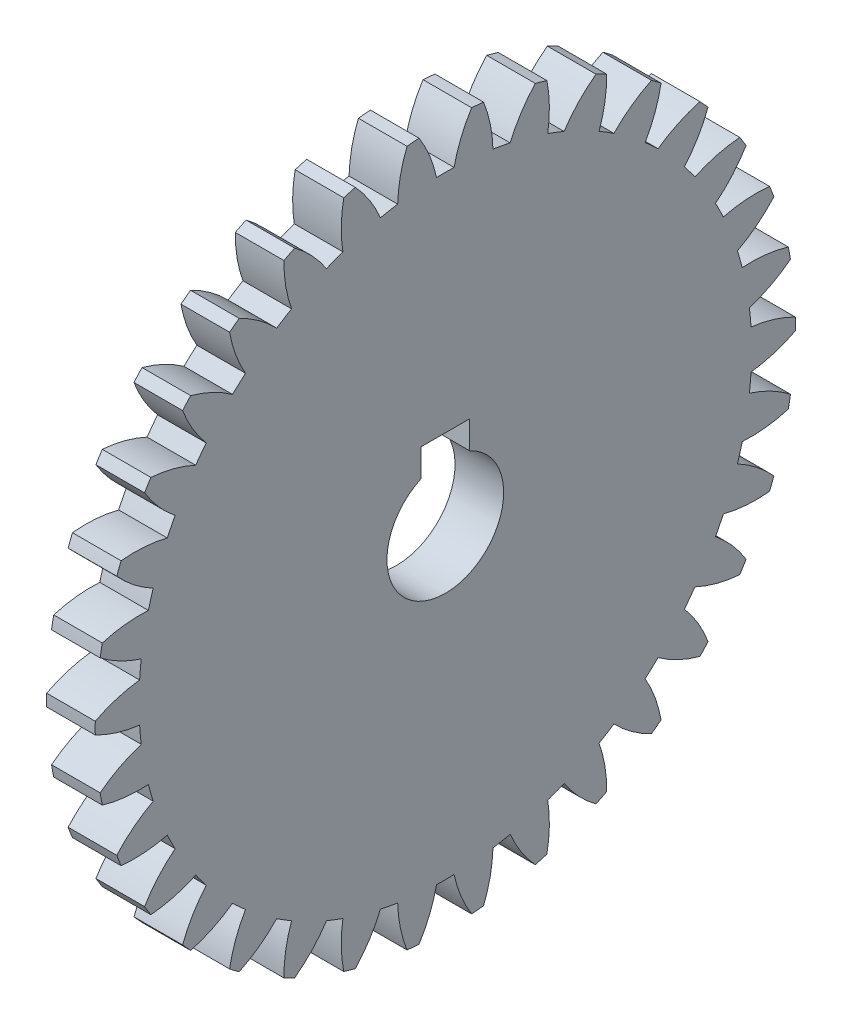
SolidWorks part; units mm, degrees
ref_plane "Plane1" through (0, 0, 0) normal (0, 0, 1) x (1, 0, 0)
ref_plane "Plane2" through (0, 0, 0) normal (0, 1, 0) x (1, 0, 0)
ref_plane "Plane3" through (0, 0, 0) normal (1, 0, 0) x (0, 0, -1)
other "Configuration Table"
sketch "HoldingSke" plane through (0, 0, 0) normal (0, 1, 0) x (1, 0, 0)
  line L0 (0, 0) -> (0.4145, -0.2796)
  line L1 (-15, 0) -> (100, 0) construction
  line L2 (0, 0) -> (-2.1039, 2.3779)
  line L3 (0, 0) -> (-11.863, 4.5341)
  line L4 (0, 0) -> (7.1596, 4.8292)
  line L5 (0, 0) -> (-46.8476, -17.4728)
  line L6 (0, 0) -> (-4.1448, -2.7965)
  line L7 (-2.1039, 2.3779) -> (8.6586, 51.2059)
  line L8 (-76.2, 54.61) -> (-73.9, 54.61)
  line L9 (-71.009, 38.7566) -> (-53.1078, 45.2721)
  line L10 (-76.2, 71.12) -> (104.1128, 71.12)
  line L11 (0, 0) -> (-5, 0)
  line L12 (-76.2, 101.6) -> (-76.133, 101.6)
  line L13 (24.9733, 27.94) -> (52.9518, 28.4284)
  line L14 (24.9733, 27.94) -> (24.9743, 27.94)
  line L15 (24.9733, 27.94) -> (100.4006, 29.5858)
  line L16 (-63.627, -2) -> (-12.827, -2)
  circle A0 centre (0, 0) radius 6
  circle A1 centre (0, 0) radius 31.499
  circle A2 centre (0, 0) radius 37.5
  circle A3 centre (0, 0) radius 6
  dimension "Hub_dia" = 75
  dimension "Bore" = 12
  dimension "MBD" = 12
  dimension "Pitch" = 0.5
  dimension "Overall_len" = 50
  dimension "Thickness" = 5
  dimension "OAL" = 50.0001
  dimension "T_dim" = 2.3
  dimension "Ap" = 20
  dimension "H" = 19.05
  dimension "Pitch_radius" = 180.3128
  dimension "Width" = 5
  dimension "Backlash" = 0.067
  dimension "Addendum_fac" = 1
  dimension "Dedendum_fac" = 1.25
  dimension "Clearance_fac" = 0.25
  dimension "Dedendum_add" = 0.001
  dimension "Module" = 2
sketch "BasProSke" plane through (0, 0, 0) normal (0, 1, 0) x (1, 0, 0)
  line L0 (-10, 0) -> (60, 0) construction
  line L1 (0, 0) -> (0, 36)
  line L2 (0, 0) -> (5, 0)
  line L3 (5, 0) -> (5, 36)
  line L4 (5, 36) -> (0, 36)
  dimension "Thickness" = 5
revolve "Base-Revolve" add sketch "BasProSke" angle 360 about L0
sketch "TooCutSke" plane through (0, 0, 0) normal (1, 0, 0) x (0, 0, -1)
  line L1 (0, 0) -> (0, 107) construction
  line L2 (0, 0) -> (-1.6875, 33.9581) construction
  line L3 (0, 0) -> (-6.2685, 67.6481) construction
  line L4 (-1.6875, 33.9581) -> (-3.1343, 33.824) construction
  arc A0 (0.9019, 31.4861) -> (-0.9019, 31.4861) centre (0, 0) ccw
  arc A1 (2.7224, 35.9224) -> (-2.7224, 35.9224) centre (0, 0) ccw
  circle A2 centre (0, 0) radius 34 construction
  circle A3 centre (0, 0) radius 31.9495 construction
  arc A4 (-0.9019, 31.4861) -> (-2.7224, 35.9224) centre (-14.1969, 28.622) ccw
  arc A5 (2.7224, 35.9224) -> (0.9019, 31.4861) centre (14.1969, 28.622) ccw
  dimension "Half_CT" = 1.453
extrude "ToothCut" cut sketch "TooCutSke" along normal through all
fillet "Breaks" [suppressed] radius 0.04
fillet "RootFillets" [suppressed] radius 0.501
pattern_circular "TeethCuts" count 34 every 10.588 about axis through (-10, 0, 0) along (1, 0, 0) of "ToothCut", "RootFillets", "Breaks"
sketch "HubNeaOneSke" plane through (0, 0, 0) normal (-1, 0, 0) x (0, 0, 1)
  circle A0 centre (0, 0) radius 31.499
extrude "HubNearOne" [suppressed] add sketch "HubNeaOneSke" along normal blind 45.0001
sketch "HubNeaBotSke" plane through (0, 0, 0) normal (-1, 0, 0) x (0, 0, 1)
  circle A0 centre (0, 0) radius 31.499
extrude "HubNearBoth" [suppressed] add sketch "HubNeaBotSke" along normal blind 22.5
ref_plane "FarPln" through (5, 0, 0) normal (1, 0, 0) x (0, 0, -1)
sketch "HubFarSke" plane through (5, 0, 0) normal (1, 0, 0) x (0, 0, -1)
  circle A0 centre (0, 0) radius 31.499
extrude "HubFar" [suppressed] add sketch "HubFarSke" along normal blind 22.5
sketch "BorSke" plane through (0, 0, 0) normal (1, 0, 0) x (0, 0, -1)
  circle A0 centre (0, 0) radius 6
  dimension "Diameter" = 12
extrude "Bore" cut sketch "BorSke" along normal mid plane 100.0001
sketch "KeySke" plane through (0, 0, 0) normal (1, 0, 0) x (0, 0, -1)
  line L0 (-2.5, 0) -> (-2.5, 8.3)
  line L1 (-2.5, 8.3) -> (2.5, 8.3)
  line L2 (2.5, 8.3) -> (2.5, 0)
  line L3 (0, 0) -> (0, 34) construction
  line L4 (-2.5, 0) -> (2.5, 0)
  dimension "Width" = 5
  dimension "Offset" = 8.3
extrude "Keyway" cut sketch "KeySke" along normal mid plane 100.0001
pattern_circular "Keyway2" [suppressed] count 2 every 90 about axis through (-10, 0, 0) along (1, 0, 0)
equation "' \"Module@HoldingSke\" = 6.35"
equation "' \"Num_teeth@HoldingSke\" = 12"
equation "' \"Ap@HoldingSke\" =  20"
equation "' \"Ap@HoldingSke\" = 20"
equation "' \"Width@HoldingSke\" = 0.5 * 25.4"
equation "' \"Hub_dia@HoldingSke\"= 1 * 25.4"
equation "' \"Hub_dia@HoldingSke\" = 1 * 25.4"
equation "' \"Overall_len@HoldingSke\" = 1.0 * 25.4"
equation "' \"Bore@HoldingSke\" = 0.75 * 25.4"
equation "' \"T_dim@HoldingSke\" = 0.1 * 25.4"
equation "' \"Width@KeySke\" = 0.25 * 25.4"
equation "' \"Show_teeth@HoldingSke\" = 13"
equation "' \"Backlash@HoldingSke\" = 0.009 * 25.4"
equation "' \"Addendum_fac@HoldingSke\" = 1.0"
equation "' \"Dedendum_fac@HoldingSke\" = 1.25"
equation "' \"Dedendum_add@HoldingSke\" = 0.00005 * 25.4"
equation "' \"Clearance_fac@HoldingSke\" = 0.25"
equation "\"Pitch@HoldingSke\" = 1 / \"Module@HoldingSke\""
equation "\"Overcut_dia@TooCutSke\" = (\"Num_teeth@HoldingSke\" + 2 * \"Addendum_fac@HoldingSke\") / \"Pitch@HoldingSke\" + 0.002 * 25.4"
equation "\"Pitch_dia@TooCutSke\" = \"Num_teeth@HoldingSke\" / \"Pitch@HoldingSke\""
equation "\"Base_dia@TooCutSke\" = \"Num_teeth@HoldingSke\" / \"Pitch@HoldingSke\" * cos((\"Ap@HoldingSke\"  * 3.14159265 / 180))"
equation "\"Root_dia@TooCutSke\" = (\"Num_teeth@HoldingSke\" + 2) / \"Pitch@HoldingSke\" - 2 * (\"Addendum_fac@HoldingSke\" + \"Dedendum_fac@HoldingSke\") / \"Pitch@HoldingSke\" - \"Dedendum_add@HoldingSke\" * 2"
equation "\"Half_ang@TooCutSke\" = 180 / \"Num_teeth@HoldingSke\""
equation "\"Half_CT@TooCutSke\" = \"Num_teeth@HoldingSke\" / \"Pitch@HoldingSke\" * sin((3.14159265 / 2 / \"Num_teeth@HoldingSke\")) / 2 - 7 * \"Backlash@HoldingSke\" / 4"
equation "\"Flank_rad@TooCutSke\" = \"Num_teeth@HoldingSke\" / \"Pitch@HoldingSke\" / 5"
equation "\"Radius@RootFillets\" = \"Clearance_fac@HoldingSke\" / \"Pitch@HoldingSke\" + \"Dedendum_add@HoldingSke\""
equation "\"Break_rad@Breaks\" = 0.02 / \"Pitch@HoldingSke\""
equation "\"Thickness@HoldingSke\" = \"Width@HoldingSke\""
equation "\"OAL@HoldingSke\" = \"Thickness@HoldingSke\""
equation "\"MHD@HoldingSke\" = (\"Num_teeth@HoldingSke\" + 2) / \"Pitch@HoldingSke\" - 2 * (\"Addendum_fac@HoldingSke\" + \"Dedendum_fac@HoldingSke\")  / \"Pitch@HoldingSke\" - \"Dedendum_add@HoldingSke\" * 2"
equation "\"MBD@HoldingSke\" = (\"Num_teeth@HoldingSke\" + 2) / \"Pitch@HoldingSke\" - 2 * (\"Addendum_fac@HoldingSke\" + \"Dedendum_fac@HoldingSke\")  / \"Pitch@HoldingSke\" - \"Dedendum_add@HoldingSke\" * 2 - 0.002 * 25.4"
equation "\"MHD@HoldingSke\" = ((sgn( \"MHD@HoldingSke\" - \"Hub_dia@HoldingSke\" )-1)*( \"MHD@HoldingSke\" - \"Hub_dia@HoldingSke\" ))/-2+ \"Hub_dia@HoldingSke\""
equation "\"MBD@HoldingSke\" = ((sgn( \"MBD@HoldingSke\" - \"Bore@HoldingSke\" )-1)*( \"MBD@HoldingSke\" - \"Bore@HoldingSke\" ))/-2+ \"Bore@HoldingSke\""
equation "\"OAL@HoldingSke\" = ((sgn( \"OAL@HoldingSke\" - \"Overall_len@HoldingSke\" )+1)*( \"OAL@HoldingSke\" - \"Overall_len@HoldingSke\" ))/2 + \"Overall_len@HoldingSke\" + 0.000002 * 25.4"
equation "\"Num_teeth@TeethCuts\" = int( \"Show_teeth@HoldingSke\" ) + 1"
equation "\"Num_teeth@TeethCuts\" = ((sgn( \"Num_teeth@TeethCuts\" - \"Num_teeth@HoldingSke\" )-1)*( \"Num_teeth@TeethCuts\" - \"Num_teeth@HoldingSke\" ))/-2+ \"Num_teeth@HoldingSke\""
equation "\"Num_teeth@TeethCuts\" = ((sgn( \"Num_teeth@TeethCuts\" - 2.0)+1)*( \"Num_teeth@TeethCuts\" - 2.0))/2 +2.0"
equation "\"Angle@TeethCuts\" = 360.0 / \"Num_teeth@HoldingSke\""
equation "\"Diameter@BasProSke\" = (\"Num_teeth@HoldingSke\" + 2 * \"Addendum_fac@HoldingSke\") / \"Pitch@HoldingSke\""
equation "\"Thickness@BasProSke\"  = \"Thickness@HoldingSke\""
equation "' \"Fillet_rad@BasProSke\" =  \"Thickness@HoldingSke\" * 0.05"
equation "' \"Fillet_rad@BasProSke\" = \"Thickness@HoldingSke\" * 0.05"
equation "\"MHD@HoldingSke\" = ((sgn( \"MHD@HoldingSke\" - \"Root_dia@TooCutSke\" )-1)*( \"MHD@HoldingSke\" - \"Root_dia@TooCutSke\" ))/-2+ \"Root_dia@TooCutSke\""
equation "\"Diameter@HubNeaOneSke\" = \"MHD@HoldingSke\""
equation "\"Length@HubNearOne\" = \"OAL@HoldingSke\" - \"Thickness@BasProSke\""
equation "\"Diameter@HubNeaBotSke\" = \"MHD@HoldingSke\""
equation "\"Length@HubNearBoth\" = ( \"OAL@HoldingSke\" - \"Thickness@BasProSke\" ) / 2.0"
equation "\"Thickness@FarPln\" = \"Thickness@BasProSke\""
equation "\"Diameter@HubFarSke\" = \"MHD@HoldingSke\""
equation "\"Length@HubFar\" = ( \"OAL@HoldingSke\" - \"Thickness@BasProSke\" ) / 2.0"
equation "\"Diameter@BorSke\" = \"MBD@HoldingSke\""
equation "\"D1@Bore\" = \"OAL@HoldingSke\" * 2.0"
equation "\"D1@Keyway\" = \"OAL@HoldingSke\" * 2.0"
equation "\"Offset@KeySke\" = \"T_dim@HoldingSke\" + \"MBD@HoldingSke\" / 2.0"
